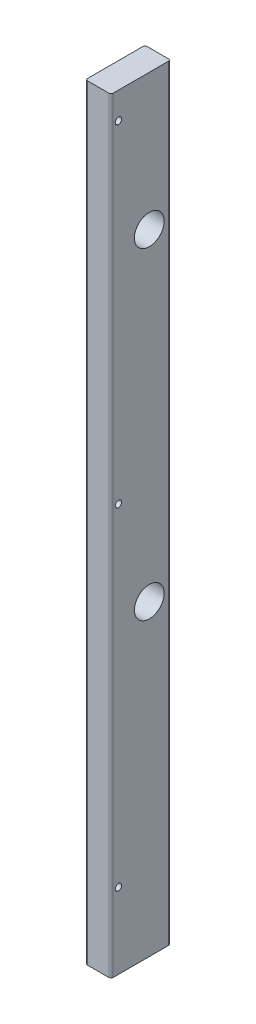
SolidWorks part; units mm, degrees
ref_plane "Front" through (0, 0, 0) normal (0, 0, 1) x (1, 0, 0)
ref_plane "Top" through (0, 0, 0) normal (0, 1, 0) x (1, 0, 0)
ref_plane "Right" through (0, 0, 0) normal (1, 0, 0) x (0, 0, -1)
sketch "Sketch1" plane through (0, 0, 0) normal (0, 1, 0) x (1, 0, 0)
  line L1 (-19.05, -44.45) -> (19.05, -44.45)
  line L2 (-19.05, -44.45) -> (-19.05, 44.45)
  line L3 (-19.05, 44.45) -> (19.05, 44.45)
  line L4 (19.05, -44.45) -> (19.05, 44.45)
  line L5 (-19.05, -44.45) -> (19.05, 44.45) construction
  line L6 (-19.05, 44.45) -> (19.05, -44.45) construction
  point P0 (0, 0)
  dimension "D1" = 38.1
  dimension "D2" = 88.9
extrude "Boss-Extrude1" add sketch "Sketch1" along normal blind 1143
sketch "Sketch2" plane through (19.05, 0, 0) normal (1, 0, 0) x (0, 0, -1)
  line L0 (-44.45, 0) -> (44.45, 0) construction
  line L1 (44.45, 1143) -> (44.45, 0) construction
  circle A0 centre (12.7, 458.7875) radius 22.225
  circle A1 centre (12.7, 939.8) radius 22.225
  dimension "D1" = 44.45
  dimension "D2" = 31.75
  dimension "D3" = 458.7875
  dimension "D4" = 481.0125
extrude "Cut-Extrude4" cut sketch "Sketch2" against normal blind 918.6545
sketch "Sketch3" plane through (19.05, 0, 0) normal (1, 0, 0) x (0, 0, -1)
  line L0 (-44.45, 1143) -> (-44.45, 0) construction
  line L2 (-44.45, 0) -> (44.45, 0) construction
  circle A0 centre (-33.3375, 112.7125) radius 4.7625
  circle A1 centre (-33.3375, 608.0125) radius 4.7625
  circle A2 centre (-33.3375, 1103.3125) radius 4.7625
  dimension "D1" = 9.525
  dimension "D2" = 11.1125
  dimension "D3" = 112.7125
  dimension "D4" = 608.0125
  dimension "D5" = 1103.3125
extrude "Cut-Extrude5" cut sketch "Sketch3" against normal through all
fillet "Fillet1" radius 3.175 4 edges at (-19.05, 571.5, -44.45) (-19.05, 571.5, 44.45) (19.05, 571.5, -44.45) (19.05, 571.5, 44.45)
